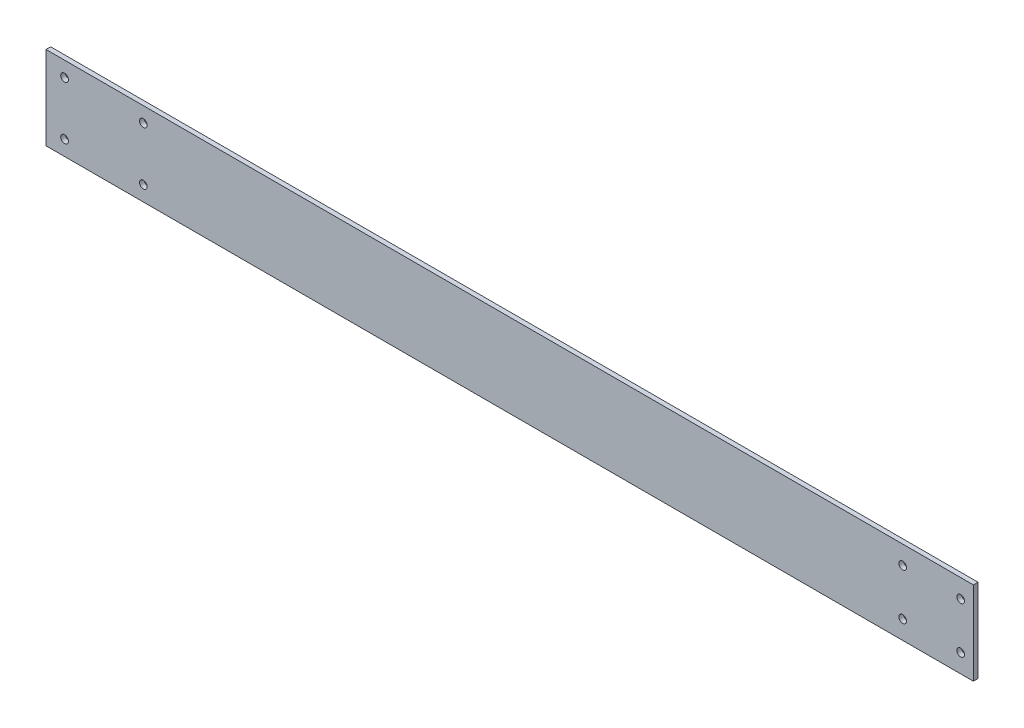
SolidWorks part; units mm, degrees
ref_plane "前视基准面" through (0, 0, 0) normal (0, 0, 1) x (1, 0, 0)
ref_plane "上视基准面" through (0, 0, 0) normal (0, 1, 0) x (1, 0, 0)
ref_plane "右视基准面" through (0, 0, 0) normal (1, 0, 0) x (0, 0, -1)
sketch "草图1" plane through (0, 0, 0) normal (0, 0, 1) x (1, 0, 0)
  line L0 (0, -28.3423) -> (0, -64.3423)
  line L1 (0, -64.3423) -> (400, -64.3423)
  line L2 (400, -64.3423) -> (400, -28.3423)
  line L3 (400, -28.3423) -> (0, -28.3423)
  dimension "D1" = 400
  dimension "D2" = 36
extrude "凸台-拉伸1" add sketch "草图1" along normal blind 2
sketch "草图2" plane through (0, 0, 2) normal (0, 0, 1) x (1, 0, 0)
  line L0 (0, -28.3423) -> (0, -64.3423) construction
  line L1 (-1000, -46.3423) -> (49000, -46.3423) construction
  circle A0 centre (8, -34.8423) radius 2
  circle A1 centre (42, -34.8423) radius 2
  circle A2 centre (8, -57.8423) radius 2
  circle A3 centre (42, -57.8423) radius 2
  point P7 (0, -46.3423)
  dimension "D1" = 8
  dimension "D2" = 11.5
  dimension "D3" = 34
  dimension "D4" = 23
hole_wizard "M4 螺纹孔的螺纹孔钻头1" positions "3D草图1" profile "草图3" hole size "M4" standard "GB"
sketch3d "3D草图1"
  point P0 (8, -34.8423, 2)
  point P3 (42, -34.8423, 2)
  point P6 (8, -57.8423, 2)
  point P9 (42, -57.8423, 2)
sketch "草图3" plane through (8, -34.8423, 2) normal (1, 0, 0) x (0, -1, 0)
  line L0 (0, 0) -> (0, 10.9914)
  line L1 (0, 10.9914) -> (1.65, 10)
  line L2 (1.65, 10) -> (1.65, 0)
  line L5 (1.65, 0) -> (0, 0)
  line L10 (0, 10.9914) -> (-1.65, 10) construction
  line L11 (0, -6.35) -> (0, 107.95) construction
  dimension "孔直径" = 3.3
  dimension "孔深度" = 10
  dimension "导头角度" = 118
sketch "草图4" plane through (0, 0, 2) normal (0, 0, 1) x (1, 0, 0)
  line L0 (-201000, -46.3423) -> (249000, -46.3423) construction
  line L1 (400, -64.3423) -> (400, -28.3423) construction
  circle A0 centre (394.5, -56.3423) radius 2
  circle A1 centre (369.5, -56.3423) radius 2
  circle A2 centre (394.5, -36.3423) radius 2
  circle A3 centre (369.5, -36.3423) radius 2
  dimension "D1" = 10
  dimension "D2" = 5.5
  dimension "D3" = 25
  dimension "D4" = 20
hole_wizard "M4 螺纹孔的螺纹孔钻头2" positions "3D草图2" profile "草图5" hole size "M4" standard "GB"
sketch3d "3D草图2"
  point P0 (394.5, -36.3423, 2)
  point P3 (394.5, -56.3423, 2)
  point P6 (369.5, -56.3423, 2)
  point P9 (369.5, -36.3423, 2)
sketch "草图5" plane through (394.5, -36.3423, 2) normal (1, 0, 0) x (0, -1, 0)
  line L0 (0, 0) -> (0, 10.9914)
  line L1 (0, 10.9914) -> (1.65, 10)
  line L2 (1.65, 10) -> (1.65, 0)
  line L5 (1.65, 0) -> (0, 0)
  line L10 (0, 10.9914) -> (-1.65, 10) construction
  line L11 (0, -6.35) -> (0, 107.95) construction
  dimension "孔直径" = 3.3
  dimension "孔深度" = 10
  dimension "导头角度" = 118
